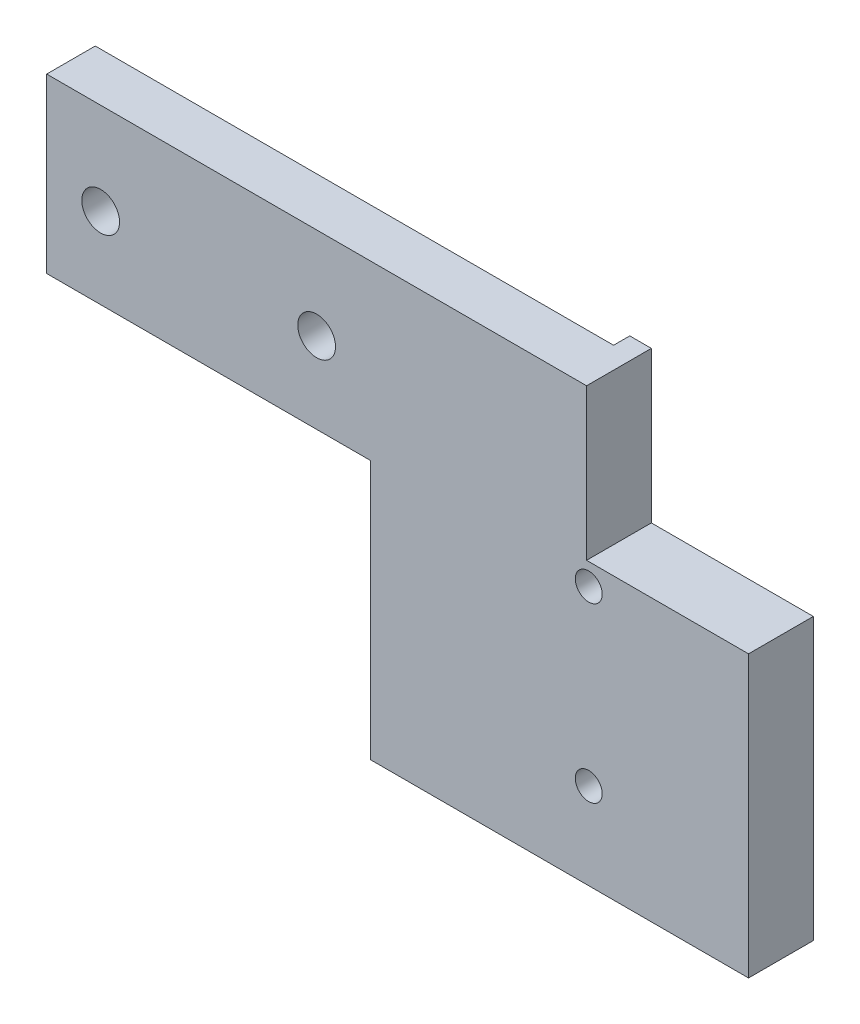
SolidWorks part; units mm, degrees
material "SKD11淬火HRC56-60"
ref_plane "前基準面" through (0, 0, 0) normal (0, 0, 1) x (1, 0, 0)
ref_plane "上基準面" through (0, 0, 0) normal (0, 1, 0) x (1, 0, 0)
ref_plane "右基準面" through (0, 0, 0) normal (1, 0, 0) x (0, 0, -1)
sketch "草图1" plane through (0, 0, 0) normal (0, 0, 1) x (1, 0, 0)
  line L1 (0, 0) -> (65, 0)
  line L2 (0, 0) -> (0, 40)
  line L3 (0, 40) -> (65, 40)
  line L4 (65, 0) -> (65, 40)
  dimension "D1" = 65
  dimension "D2" = 40
extrude "凸台-拉伸1" add sketch "草图1" along normal blind 6
sketch "草图2" plane through (0, 40, 0) normal (0, 1, 0) x (1, 0, 0)
  line L0 (65, -6) -> (65, 0) construction
  line L1 (0, 0) -> (48, 0)
  line L2 (0, 0) -> (0, -1.5)
  line L3 (0, -1.5) -> (48, -1.5)
  line L4 (48, 0) -> (48, -1.5)
  dimension "D1" = 1.5
  dimension "D2" = 17
extrude "切除-拉伸1" cut sketch "草图2" against normal through all
hole_wizard "Ø3.5 (3.5) 直径孔1" positions "草图4" profile "草图3" hole size "Ø3.5" standard "ISO"
sketch "草图4" plane through (0, 0, 6) normal (0, 0, 1) x (1, 0, 0)
  point P1 (25, 31.5)
  point P4 (5, 31.5)
sketch "草图3" plane through (25, 31.5, 6) normal (1, 0, 0) x (0, -1, 0)
  line L0 (0, 0) -> (0, 11.0515)
  line L1 (0, 11.0515) -> (1.75, 10)
  line L2 (1.75, 10) -> (1.75, 0)
  line L5 (1.75, 0) -> (0, 0)
  line L10 (0, 11.0515) -> (-1.75, 10) construction
  line L11 (0, -6.35) -> (0, 107.95) construction
  dimension "孔直径" = 3.5
  dimension "孔深度" = 10
  dimension "导头角度" = 118
hole_wizard "M3 螺纹孔1" positions "草图6" profile "草图5" tap size "M3" standard "ISO" end condition through all
sketch "草图6" plane through (0, 0, 6) normal (0, 0, 1) x (1, 0, 0)
  line L0 (65, 0) -> (65, 40) construction
  line L1 (0, 0) -> (65, 0) construction
  point P0 (50.2, 8)
  point P1 (50.2, 24)
  dimension "D1" = 16
  dimension "D2" = 14.8
  dimension "D3" = 8
sketch "草图5" plane through (50.2, 8, 6) normal (1, 0, 0) x (0, -1, 0)
  line L0 (0, 0) -> (0, 6)
  line L1 (0, 6) -> (1.25, 6)
  line L2 (1.25, 6) -> (1.25, 0)
  line L5 (1.25, 0) -> (0, 0)
  line L11 (0, -6.35) -> (0, 107.95) construction
  dimension "通孔螺纹孔钻头直径" = 2.5
  dimension "通孔螺纹孔钻头深度" = 6
cosmetic thread "孔螺蚊线1" parameters "D2"=3
cosmetic thread "孔螺蚊线2" parameters "D2"=3
sketch "草图7" plane through (0, 0, 6) normal (0, 0, 1) x (1, 0, 0)
  line L1 (0, 0) -> (30, 0)
  line L2 (0, 0) -> (0, 24)
  line L3 (0, 24) -> (30, 24)
  line L4 (30, 0) -> (30, 24)
  dimension "D1" = 24
  dimension "D2" = 30
extrude "切除-拉伸2" cut sketch "草图7" against normal blind 10
ref_plane "基准面1" through (80.5, 41.5, -18.5) normal (-1, 0, 0) x (0, 0, 1)
sketch "草图9" plane through (0, 0, 6) normal (0, 0, 1) x (1, 0, 0)
  line L1 (65, 40) -> (50, 40)
  line L2 (65, 40) -> (65, 26)
  line L3 (65, 26) -> (50, 26)
  line L4 (50, 40) -> (50, 26)
  dimension "D1" = 14
  dimension "D2" = 15
extrude "切除-拉伸3" cut sketch "草图9" against normal through all
